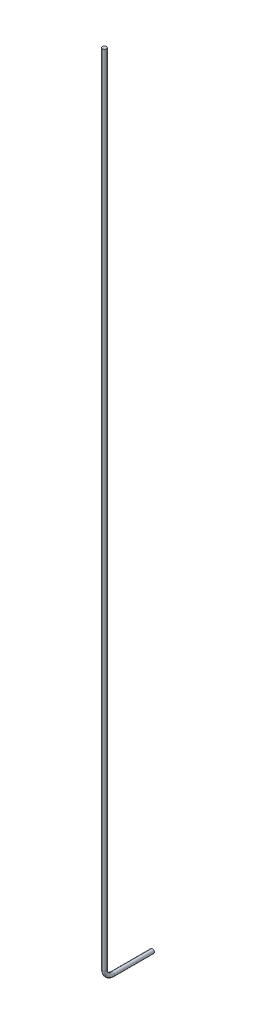
SolidWorks part; units mm, degrees
ref_plane "正面" through (0, 0, 0) normal (0, 0, 1) x (1, 0, 0)
ref_plane "平面" through (0, 0, 0) normal (0, 1, 0) x (1, 0, 0)
ref_plane "右側面" through (0, 0, 0) normal (1, 0, 0) x (0, 0, -1)
sketch "ｽｹｯﾁ1" plane through (0, 0, 0) normal (0, 0, 1) x (1, 0, 0)
  circle A0 centre (0, 0) radius 1.27
  dimension "D1" = 2.54
extrude "ﾎﾞｽ - 押し出し1" add sketch "ｽｹｯﾁ1" along normal blind 20
sketch "ｽｹｯﾁ2" plane through (0, 0, 20) normal (0, 0, 1) x (1, 0, 0)
  circle A1 centre (0, 0) radius 1.27
  circle A2 centre (0, 0) radius 1.27
  dimension "D1" = 0
sketch "ｽｹｯﾁ3" plane through (0, 0, 0) normal (1, 0, 0) x (0, 0, -1)
  line L0 (-20, 0) -> (-25, 0)
  line L1 (-20, 1.27) -> (-20, -1.27) construction
  line L2 (-30, 5) -> (-30, 505)
  line L3 (-20, 1.27) -> (-20, -1.27) construction
  arc A0 (-25, 0) -> (-30, 5) centre (-25, 5) cw
  point P8 (-30, 0)
  dimension "D2" = 5
  dimension "D1" = 10
  dimension "D3" = 500
sweep "ｽｲｰﾌﾟ1" add profiles "ｽｹｯﾁ2" path "ｽｹｯﾁ3"
